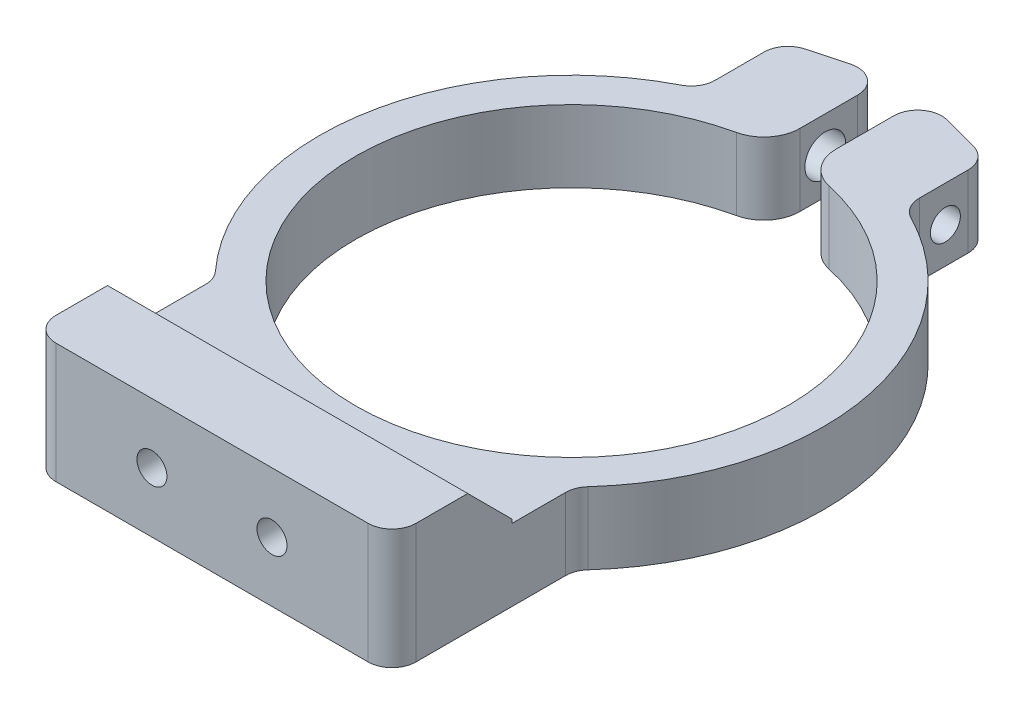
SolidWorks part; units mm, degrees
material "Сплав 2024"
ref_plane "Спереди" through (0, 0, 0) normal (0, 0, 1) x (1, 0, 0)
ref_plane "Сверху" through (0, 0, 0) normal (0, 1, 0) x (1, 0, 0)
ref_plane "Справа" through (0, 0, 0) normal (1, 0, 0) x (0, 0, -1)
sketch "Эскиз1" plane through (0, 0, 0) normal (0, 1, 0) x (1, 0, 0)
  line L0 (-15, -9.9499) -> (-15, -29.9499) construction
  line L1 (-15, -29.9499) -> (15, -29.9499) construction
  line L2 (15, -29.9499) -> (15, -9.9499) construction
  line L3 (15, -9.9499) -> (-15, -9.9499) construction
  line L4 (-15, -14.6969) -> (-15, -29.9499)
  line L5 (-15, -29.9499) -> (15, -29.9499)
  line L6 (15, -29.9499) -> (15, -14.6969)
  circle A0 centre (0, 0) radius 18
  arc A1 (15, -14.6969) -> (-15, -14.6969) centre (0, 0) ccw
  circle A3 centre (0, 0) radius 21 construction
  point P7 (-15, -14.6969)
  point P10 (15, -14.6969)
  point P12 (35.25, 0)
  dimension "D1" = 36
  dimension "D3" = 30
  dimension "D4" = 20
  dimension "D2" = 3
extrude "Бобышка-Вытянуть1" add sketch "Эскиз1" along normal blind 6
sketch "Эскиз4" plane through (0, 6, 0) normal (0, 1, 0) x (1, 0, 0)
  line L0 (0, 21) -> (0, -29.9499) construction
  line L1 (1.5, 16) -> (-1.5, 16)
  line L2 (1.5, 16) -> (1.5, 21)
  line L3 (1.5, 21) -> (-1.5, 21)
  line L4 (-1.5, 16) -> (-1.5, 21)
  line L5 (-15, -29.9499) -> (15, -29.9499) construction
  arc A1 (15, -14.6969) -> (-15, -14.6969) centre (0, 0) ccw construction
  dimension "D1" = 3
  dimension "D2" = 5
extrude "Вырез-Вытянуть2" cut sketch "Эскиз4" against normal up to surface (6 mm away) up to face at (0, 0, 13.3992)
sketch "Эскиз20" plane through (0, 6, 0) normal (0, 1, 0) x (1, 0, 0)
  line L0 (15, -29.9499) -> (15, -14.6969) construction
  line L1 (-15, -29.9499) -> (15, -29.9499)
  line L2 (-15, -29.9499) -> (-15, -19.9499)
  line L3 (-15, -19.9499) -> (15, -19.9499)
  line L4 (15, -29.9499) -> (15, -19.9499)
  dimension "D1" = 10
extrude "Бобышка-Вытянуть6" add sketch "Эскиз20" along normal blind 4
sketch "Эскиз11" plane through (0, 6, 0) normal (0, 1, 0) x (1, 0, 0)
  line L0 (0, 21.0139) -> (0, -29.9499) construction
  line L1 (-1.5, 17.9374) -> (-8.5, 17.9374)
  line L2 (-1.5, 17.9374) -> (-1.5, 27.9374)
  line L3 (-1.5, 27.9374) -> (-8.5, 26.0617)
  line L4 (-8.5, 17.9374) -> (-8.5, 26.0617)
  line L5 (-15, -29.9499) -> (15, -29.9499) construction
  line L6 (8.5, 17.9374) -> (8.5, 26.0617)
  line L7 (1.5, 27.9374) -> (8.5, 26.0617)
  line L8 (1.5, 17.9374) -> (1.5, 27.9374)
  line L9 (1.5, 17.9374) -> (8.5, 17.9374)
  dimension "D1" = 7
  dimension "D2" = 75
  dimension "D3" = 10
extrude "Бобышка-Вытянуть5" add sketch "Эскиз11" against normal up to surface (6 mm away) up to face at (0, 0, 4.8546)
sketch "Эскиз12" plane through (-8.5, 0, 0) normal (-1, 0, 0) x (0, 0, 1)
  line L0 (-26.0617, 3) -> (-19.2029, 3) construction
  line L1 (-26.0617, 0) -> (-26.0617, 6) construction
  line L2 (-19.2029, 0) -> (-19.2029, 6) construction
  line L3 (-22.6323, 6) -> (-22.6323, 0) construction
  line L4 (-26.0617, 6) -> (-19.2029, 6) construction
  line L5 (-19.2029, 0) -> (-26.0617, 0) construction
ref_plane "Плоскость1" through (8.5, 0, 0) normal (1, 0, 0) x (0, 0, -1)
ref_plane "Плоскость2" through (-8.5, 0, 0) normal (-1, 0, 0) x (0, 0, 1)
hole_wizard "Отверстие с зазором M32" positions "Эскиз14" profile "Эскиз13" hole size "M3" standard "Ansi Metric"
sketch "Эскиз14" plane through (-8.5, 0, 0) normal (-1, 0, 0) x (0, 0, 1)
  line L1 (-22.6323, 6) -> (-22.6323, 0) construction
  line L2 (-26.0617, 3) -> (-19.2029, 3) construction
  point P0 (-22.6323, 3)
sketch "Эскиз13" plane through (-8.5, 3, -22.6323) normal (0, 1, 0) x (0, 0, 1)
  line L0 (0, 0) -> (0, 7)
  line L1 (0, 7) -> (1.7, 7)
  line L2 (1.7, 7) -> (1.7, 0)
  line L5 (1.7, 0) -> (0, 0)
  line L11 (0, -6.35) -> (0, 107.95) construction
  dimension "Диаметр сквозного отверстия" = 3.4
  dimension "Глубина сквозного отверстия" = 7
hole_wizard "Отверстие обработанное метчиком M3x0.51" positions "Эскиз16" profile "Эскиз15" tap size "M3x0.5" standard "Ansi Metric" end condition through all
sketch "Эскиз16" plane through (1.5, -0.9107, -4.3934) normal (-1, 0, 0) x (0, 0, 1)
  line L1 (-18.2389, 6.9107) -> (-18.2389, 0.9107) construction
  line L2 (-21.6683, 3.9107) -> (-14.8095, 3.9107) construction
  point P0 (-18.2389, 3.9107)
cosmetic thread "Отверстие резьбы5" parameters "D2"=3
sketch "Эскиз15" plane through (1.5, 3, -22.6323) normal (0, 1, 0) x (0, 0, 1)
  line L0 (0, 0) -> (0, 19.5)
  line L1 (0, 19.5) -> (1.25, 19.5)
  line L2 (1.25, 19.5) -> (1.25, 0)
  line L5 (1.25, 0) -> (0, 0)
  line L11 (0, -6.35) -> (0, 107.95) construction
  dimension "Диаметр проходного сверла" = 2.5
  dimension "Глубина проходного сверла" = 19.5
sketch "Эскиз17" plane through (0, 0, 29.9499) normal (0, 0, 1) x (1, 0, 0)
  line L0 (-15, 5) -> (15, 5) construction
  line L1 (-15, 10) -> (-15, 0) construction
  line L2 (15, 10) -> (15, 0) construction
  line L3 (-5, 10) -> (-5, 0) construction
  line L5 (-15, 0) -> (15, 0) construction
  line L6 (5, 10) -> (5, 0) construction
  line L7 (-15, 6) -> (-15, 0) construction
  line L9 (-15, 10) -> (15, 10) construction
  dimension "D1" = 10
  dimension "D2" = 30
  dimension "D3" = 10
hole_wizard "Отверстие обработанное метчиком M3x0.52" positions "Эскиз19" profile "Эскиз18" tap size "M3x0.5" standard "Ansi Metric"
sketch "Эскиз19" plane through (0, 0, 29.9499) normal (0, 0, 1) x (1, 0, 0)
  line L0 (-5, 10) -> (-5, 0) construction
  line L1 (5, 10) -> (5, 0) construction
  point P0 (-5, 5)
  point P4 (5, 5)
sketch "Эскиз18" plane through (-5, 5, 29.9499) normal (1, 0, 0) x (0, -1, 0)
  line L0 (0, 0) -> (0, 9.2511)
  line L1 (0, 9.2511) -> (1.25, 8.5)
  line L2 (1.25, 8.5) -> (1.25, 0)
  line L5 (1.25, 0) -> (0, 0)
  line L10 (0, 9.2511) -> (-1.25, 8.5) construction
  line L11 (0, -6.35) -> (0, 107.95) construction
  dimension "Диаметр сверла" = 2.5
  dimension "Глубина сверла" = 8.5
  dimension "Угол заточки сверла" = 118
cosmetic thread "Отверстие резьбы2" parameters "D1"=7, "D2"=3
cosmetic thread "Отверстие резьбы3" parameters "D1"=7, "D2"=3
fillet "Скругление1" radius 2 10 edges at (15, 3, 14.6969) (-8.5, 3, -19.2029) (8.5, 3, -19.2029) (15, 5, 29.9499) (-15, 5, 29.9499) (-15, 3, 14.6969) (8.5, 3, -26.0617) (1.5, 3, -27.9374) (-1.5, 3, -27.9374) (-8.5, 3, -26.0617)
fillet "Скругление2" radius 3 2 edges at (1.5, 3, -17.9374) (-1.5, 3, -17.9374)
chamfer "Фаска1" distance 3.7 distance2 3.7 1 edges at (0, 10, 19.9499)
equation "\"D1@Эскиз17\"=\"D2@Эскиз17\"/3"
equation "\"D3@Эскиз17\"=\"D1@Эскиз17\""
